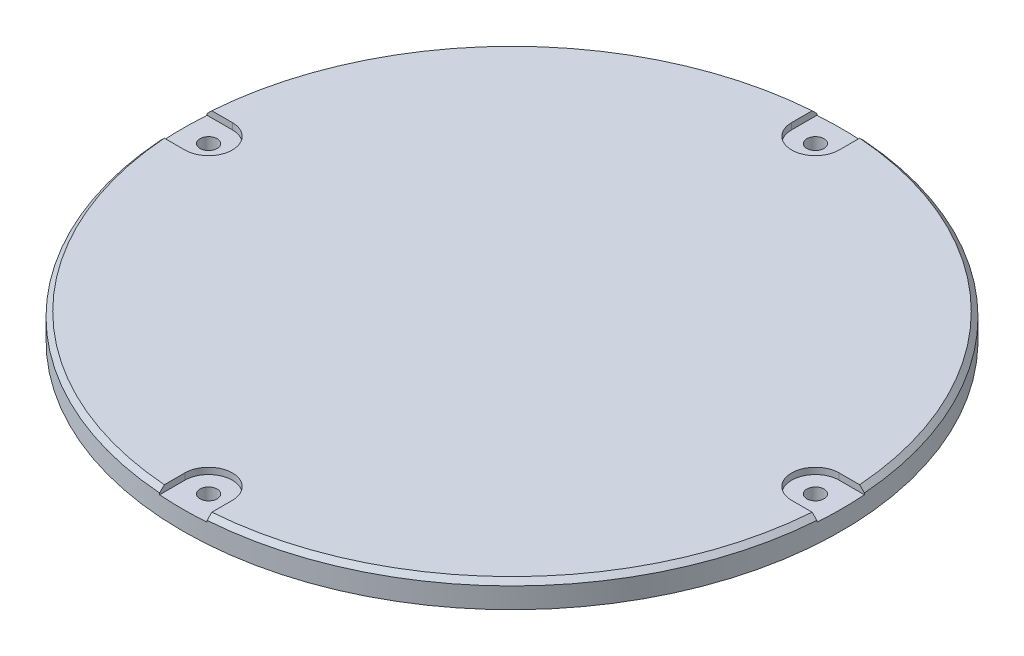
SolidWorks part; units mm, degrees
ref_plane "Front Plane" through (0, 0, 0) normal (0, 0, 1) x (1, 0, 0)
ref_plane "Top Plane" through (0, 0, 0) normal (0, 1, 0) x (1, 0, 0)
ref_plane "Right Plane" through (0, 0, 0) normal (1, 0, 0) x (0, 0, -1)
sketch "Sketch1" plane through (0, 0, 0) normal (0, 1, 0) x (1, 0, 0)
  circle A0 centre (0, 0) radius 52
  dimension "D1" = 104
extrude "Boss-Extrude1" add sketch "Sketch1" along normal blind 4
sketch "Sketch2" plane through (0, 4, 0) normal (0, 1, 0) x (1, 0, 0)
  line L0 (0, 46.53) -> (0, 52) construction
  circle A1 centre (0, 47.88) radius 1.35
  circle A4 centre (47.88, 0) radius 1.35
  circle A5 centre (0, 0) radius 52 construction
  circle A6 centre (0, -47.88) radius 1.35
  circle A7 centre (-47.88, 0) radius 1.35
  dimension "D1" = 4.12
  dimension "D2" = 2.7
  dimension "D3" = 4
extrude "Cut-Extrude2" cut sketch "Sketch2" against normal blind 3
chamfer "Chamfer1" distance 0.75 angle 45 1 edges at (0, 4, 52)
sketch "Sketch3" plane through (0, 4, 0) normal (0, 1, 0) x (1, 0, 0)
  line L0 (0, 52) -> (0, -52) construction
  line L1 (-52, 0) -> (52, 0) construction
  line L2 (-3.75, 51.8646) -> (-3.75, 47.88)
  line L3 (3.75, 51.8646) -> (3.75, 47.88)
  line L4 (51.8646, 3.75) -> (47.88, 3.75)
  line L5 (51.8646, -3.75) -> (47.88, -3.75)
  line L6 (3.75, -51.8646) -> (3.75, -47.88)
  line L7 (-3.75, -51.8646) -> (-3.75, -47.88)
  line L8 (-51.8646, -3.75) -> (-47.88, -3.75)
  line L9 (-51.8646, 3.75) -> (-47.88, 3.75)
  arc A0 (-51.8646, 3.75) -> (-51.8646, -3.75) centre (0, 0) ccw
  circle A1 centre (47.88, 0) radius 1.35
  arc A2 (-3.75, 47.88) -> (3.75, 47.88) centre (0, 47.88) ccw
  circle A3 centre (0, 47.88) radius 1.35 construction
  arc A4 (-51.8646, 3.75) -> (-51.8646, -3.75) centre (0, 0) ccw
  arc A5 (47.88, 3.75) -> (47.88, -3.75) centre (47.88, 0) ccw
  arc A6 (-51.8646, 3.75) -> (-51.8646, -3.75) centre (0, 0) ccw
  arc A7 (3.75, -47.88) -> (-3.75, -47.88) centre (0, -47.88) ccw
  arc A8 (-51.8646, 3.75) -> (-51.8646, -3.75) centre (0, 0) ccw
  arc A9 (-47.88, -3.75) -> (-47.88, 3.75) centre (-47.88, 0) ccw
  arc A10 (-3.75, -51.8646) -> (3.75, -51.8646) centre (0, 0) ccw
  arc A11 (-3.75, -51.8646) -> (3.75, -51.8646) centre (0, 0) ccw
  arc A12 (-3.75, -51.8646) -> (3.75, -51.8646) centre (0, 0) ccw
  arc A13 (-3.75, -51.8646) -> (3.75, -51.8646) centre (0, 0) ccw
  arc A14 (51.8646, -3.75) -> (51.8646, 3.75) centre (0, 0) ccw
  arc A15 (51.8646, -3.75) -> (51.8646, 3.75) centre (0, 0) ccw
  arc A16 (51.8646, -3.75) -> (51.8646, 3.75) centre (0, 0) ccw
  arc A17 (51.8646, -3.75) -> (51.8646, 3.75) centre (0, 0) ccw
  arc A18 (3.75, 51.8646) -> (-3.75, 51.8646) centre (0, 0) ccw
  arc A19 (3.75, 51.8646) -> (-3.75, 51.8646) centre (0, 0) ccw
  arc A20 (3.75, 51.8646) -> (-3.75, 51.8646) centre (0, 0) ccw
  arc A21 (3.75, 51.8646) -> (-3.75, 51.8646) centre (0, 0) ccw
  circle A22 centre (0, 47.88) radius 1.35
  circle A23 centre (0, -47.88) radius 1.35
  circle A24 centre (-47.88, 0) radius 1.35
  circle M1 centre (0, 0) radius 51.25
  circle M2 centre (0, 47.88) radius 1.35
  circle M3 centre (47.88, 0) radius 1.35
  circle M4 centre (0, -47.88) radius 1.35
  circle M5 centre (-47.88, 0) radius 1.35
  dimension "D1" = 104
  dimension "D3" = 4
  dimension "D4" = 2.7
  dimension "D2" = 7.5
  dimension "D5" = 4
extrude "Cut-Extrude3" cut sketch "Sketch3" against normal blind 1 contours L2 A2 L3 M1 M2 | L8 A9 L9 M1 M5 | L4 A5 L5 M1 M3 | L3 A18 L2 M1 | L9 A0 L8 M1 | L5 A14 L4 M1 | L6 A7 L7 M1 M4 | L7 A10 L6 M1
